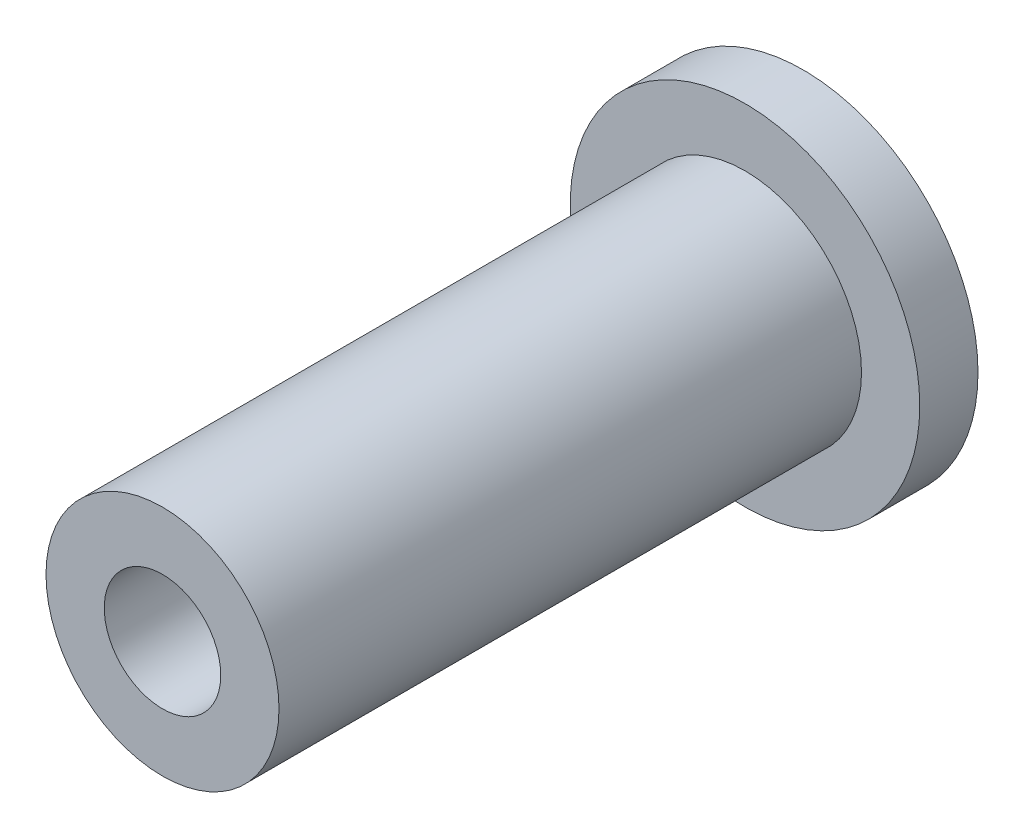
SolidWorks part; units mm, degrees
ref_plane "Front Plane" through (0, 0, 0) normal (1, 0, 0) x (0, 1, 0)
ref_plane "Top Plane" through (0, 0, 0) normal (0, 0, 1) x (0, 1, 0)
ref_plane "Right Plane" through (0, 0, 0) normal (0, 1, 0) x (-1, 0, 0)
sketch "Sketch2" plane through (0, 0, 0) normal (0, 0, 1) x (0, 1, 0)
  circle A0 centre (0, 0) radius 10
  circle A1 centre (0, 0) radius 20
  dimension "D1" = 20
  dimension "D2" = 40
extrude "Boss-Extrude1" add sketch "Sketch2" along normal blind 110
sketch "Sketch3" plane through (0, 0, 0) normal (0, 0, 1) x (0, 1, 0)
  circle A0 centre (0, 0) radius 30
  dimension "D1" = 60
extrude "Boss-Extrude2" add sketch "Sketch3" along normal blind 10
sketch "Sketch4" plane through (0, 0, 10) normal (0, 0, 1) x (1, 0, 0)
  circle A0 centre (0, 0) radius 10
extrude "Cut-Extrude1" cut sketch "Sketch4" against normal blind 10
